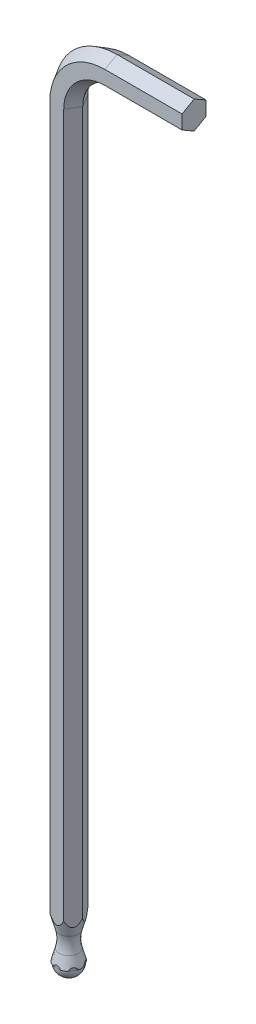
SolidWorks part; units mm, degrees
ref_plane "Vorne" through (0, 0, 0) normal (0, 0, 1) x (1, 0, 0)
ref_plane "Oben" through (0, 0, 0) normal (0, 1, 0) x (1, 0, 0)
ref_plane "Rechts" through (0, 0, 0) normal (1, 0, 0) x (0, 0, -1)
sketch "Skizze1" plane through (0, 0, 0) normal (0, 0, 1) x (1, 0, 0)
  line L0 (0, 0) -> (0, 155)
  line L1 (10, 165) -> (26, 165)
  arc A0 (0, 155) -> (10, 165) centre (10, 155) cw
  point P6 (0, 165)
  dimension "D3" = 10
  dimension "D1" = 165
  dimension "D2" = 26
sketch "Skizze3" plane through (0, 0, 0) normal (0, 1, 0) x (1, 0, 0)
  line L0 (-2.8868, 0) -> (2.8868, 0) construction
  line L1 (-1.4434, 2.5) -> (-2.8868, 0)
  line L2 (-2.8868, 0) -> (-1.4434, -2.5)
  line L3 (-1.4434, -2.5) -> (1.4434, -2.5)
  line L4 (1.4434, -2.5) -> (2.8868, 0)
  line L5 (2.8868, 0) -> (1.4434, 2.5)
  line L6 (1.4434, 2.5) -> (-1.4434, 2.5)
  circle A0 centre (0, 0) radius 2.5 construction
  dimension "D1" = 5
sweep "Austragung4" add profiles "Skizze3" path "Skizze1"
sketch "Skizze6" plane through (0, 0, 0) normal (1, 0, 0) x (0, 0, -1)
  line L0 (0, 7.8104) -> (0, -7.0578) construction
  line L1 (-2.5, 155) -> (-2.5, 0) construction
  line L2 (0, -2.5) -> (0, 2.5)
  arc A0 (0, -2.5) -> (0, 2.5) centre (0, 0) ccw
revolve "Rotation5" add sketch "Skizze6" angle 360 about L0
sketch "Skizze8" plane through (0, 0, 0) normal (0, 0, 1) x (1, 0, 0)
  line L0 (0, 0) -> (0, 50.305) construction
  line L1 (-2.8868, -0.9) -> (-1.9818, 2.3628)
  line L2 (-2.8868, 155) -> (-2.8868, 0) construction
  line L3 (-2.8868, 4.1) -> (2.8868, 4.1) construction
  line L5 (-1.9818, 5.8372) -> (-2.8868, 9.1)
  line L6 (-2.8868, 9.1) -> (-2.8868, -0.9)
  line L7 (2.8868, 155) -> (2.8868, 0) construction
  arc A0 (-1.9818, 2.3628) -> (-1.9818, 5.8372) centre (-8.2454, 4.1) ccw
  point P14 (-1.5, 4.1)
  dimension "D1" = 10
  dimension "D4" = 6.5
  dimension "D2" = 4.1
  dimension "D3" = 1.5
revolve "Schnitt-Rotation1" cut sketch "Skizze8" angle 360 about L0
